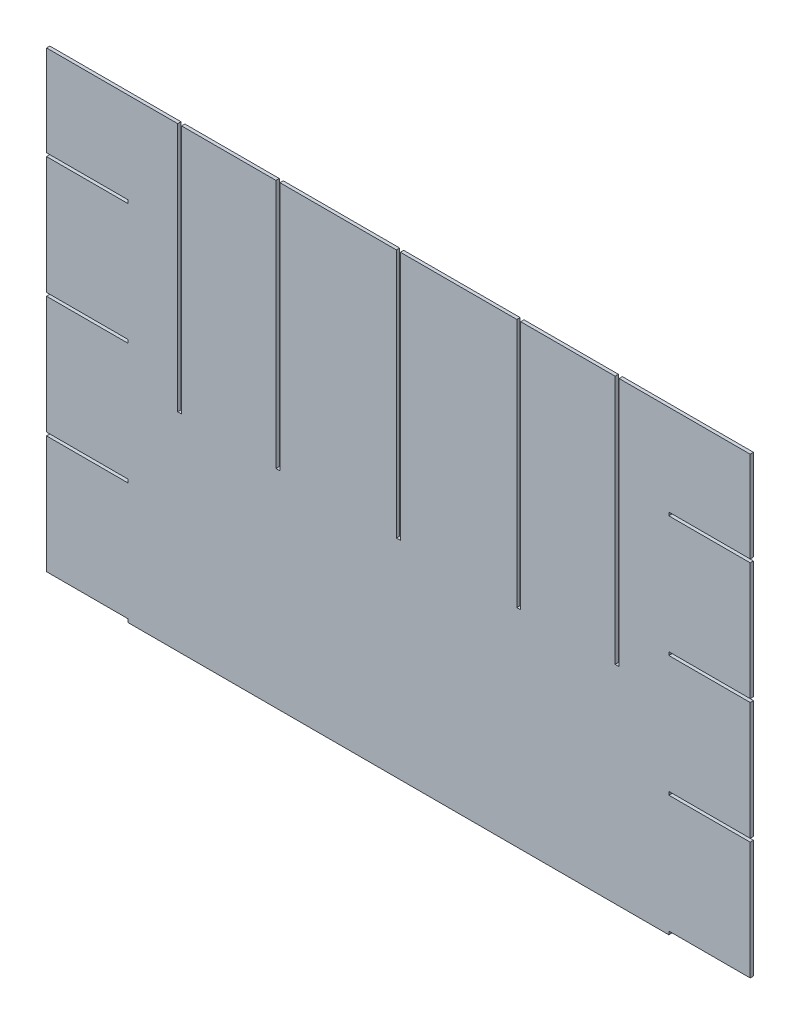
SolidWorks part; units mm, degrees
ref_plane "Front Plane" through (0, 0, 0) normal (0, 0, 1) x (1, 0, 0)
ref_plane "Top Plane" through (0, 0, 0) normal (0, 1, 0) x (1, 0, 0)
ref_plane "Right Plane" through (0, 0, 0) normal (1, 0, 0) x (0, 0, -1)
sketch "Model" plane through (0, 0, 0) normal (0, 0, 1) x (1, 0, 0)
  line L0 (-319.9846, 3) -> (-245.9797, 3)
  line L1 (-245.9797, 3) -> (-245.9797, 0)
  line L2 (245.9797, 0) -> (-245.9797, 0)
  line L3 (245.9797, 0) -> (245.9797, 3)
  line L4 (319.9846, 3) -> (245.9797, 3)
  line L5 (319.9846, 3) -> (319.9846, 110)
  line L6 (319.9846, 110) -> (245.9797, 110)
  line L7 (245.9797, 113) -> (245.9797, 110)
  line L8 (319.9846, 113) -> (245.9797, 113)
  line L9 (319.9846, 113) -> (319.9846, 220)
  line L10 (319.9846, 220) -> (245.9797, 220)
  line L11 (245.9797, 223) -> (245.9797, 220)
  line L12 (319.9846, 223) -> (245.9797, 223)
  line L13 (319.9846, 223) -> (319.9846, 330)
  line L14 (319.9846, 330) -> (245.9797, 330)
  line L15 (245.9797, 333) -> (245.9797, 330)
  line L16 (319.9846, 333) -> (245.9797, 333)
  line L17 (319.9846, 333) -> (319.9846, 415.5651)
  line L18 (200.7227, 415.5651) -> (319.9846, 415.5651)
  line L19 (200.7227, 415.5651) -> (200.7227, 188.6103)
  line L20 (200.7227, 188.6103) -> (197.1227, 188.6103)
  line L21 (197.1227, 188.6103) -> (197.1227, 415.5651)
  line L22 (111.3, 415.5651) -> (197.1227, 415.5651)
  line L23 (111.3, 415.5651) -> (111.3, 188.6103)
  line L24 (111.3, 188.6103) -> (107.7, 188.6103)
  line L25 (107.7, 188.6103) -> (107.7, 415.5651)
  line L26 (1.8, 415.5651) -> (107.7, 415.5651)
  line L27 (1.8, 415.5651) -> (1.8, 188.6103)
  line L28 (1.8, 188.6103) -> (-1.8, 188.6103)
  line L29 (-1.8, 188.6103) -> (-1.8, 415.5651)
  line L30 (-107.7, 415.5651) -> (-1.8, 415.5651)
  line L31 (-107.7, 415.5651) -> (-107.7, 188.6103)
  line L32 (-107.7, 188.6103) -> (-111.3, 188.6103)
  line L33 (-111.3, 188.6103) -> (-111.3, 415.5651)
  line L34 (-197.1227, 415.5651) -> (-111.3, 415.5651)
  line L35 (-197.1227, 415.5651) -> (-197.1227, 188.6103)
  line L36 (-197.1227, 188.6103) -> (-200.7227, 188.6103)
  line L37 (-200.7227, 188.6103) -> (-200.7227, 415.5651)
  line L38 (-319.9846, 415.5651) -> (-200.7227, 415.5651)
  line L39 (-319.9846, 333) -> (-319.9846, 415.5651)
  line L40 (-319.9846, 333) -> (-245.9797, 333)
  line L41 (-245.9797, 333) -> (-245.9797, 330)
  line L42 (-319.9846, 330) -> (-245.9797, 330)
  line L43 (-319.9846, 223) -> (-319.9846, 330)
  line L44 (-319.9846, 223) -> (-245.9797, 223)
  line L45 (-245.9797, 223) -> (-245.9797, 220)
  line L46 (-319.9846, 220) -> (-245.9797, 220)
  line L47 (-319.9846, 113) -> (-319.9846, 220)
  line L48 (-319.9846, 113) -> (-245.9797, 113)
  line L49 (-245.9797, 113) -> (-245.9797, 110)
  line L50 (-319.9846, 110) -> (-245.9797, 110)
  line L51 (-319.9846, 3) -> (-319.9846, 110)
extrude "Boss-Extrude1" add sketch "Model" along normal blind 3
